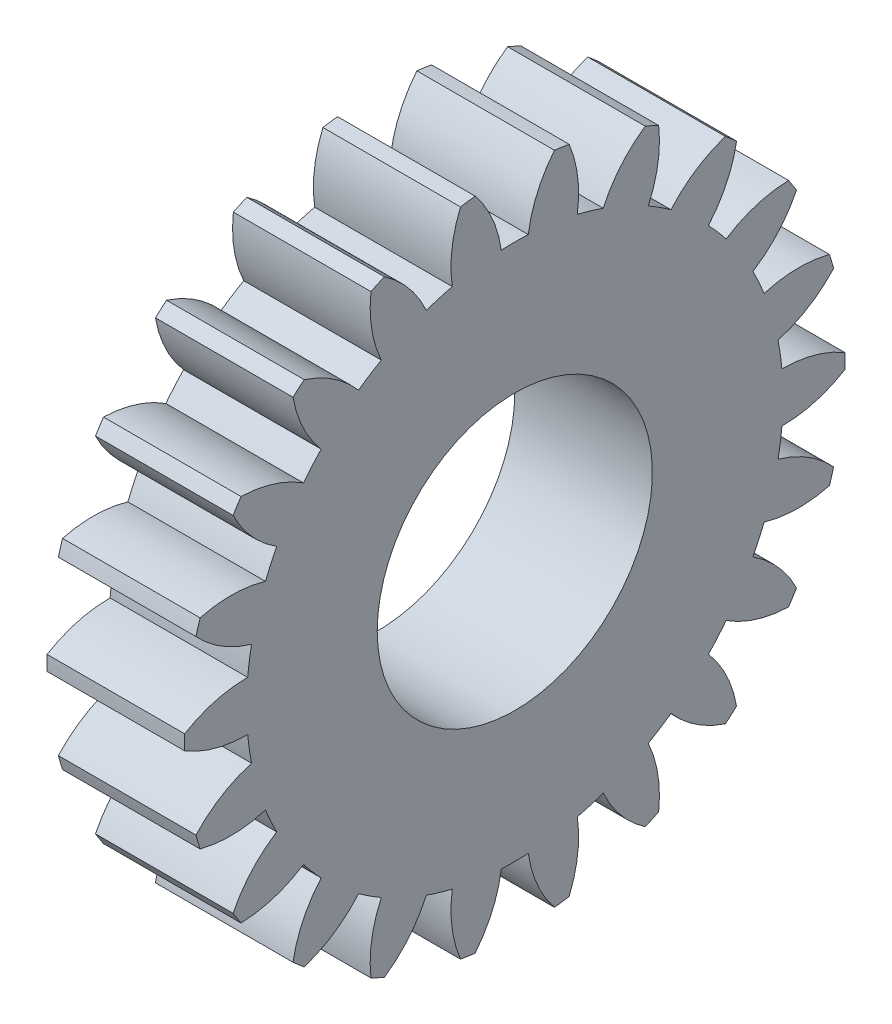
SolidWorks part; units mm, degrees
ref_plane "Plane1" through (0, 0, 0) normal (0, 0, 1) x (1, 0, 0)
ref_plane "Plane2" through (0, 0, 0) normal (0, 1, 0) x (1, 0, 0)
ref_plane "Plane3" through (0, 0, 0) normal (1, 0, 0) x (0, 0, -1)
sketch "HoldingSke" plane through (0, 0, 0) normal (0, 1, 0) x (1, 0, 0)
  line L0 (0, 0) -> (1.8544, -0.7492)
  line L1 (-15, 0) -> (100, 0) construction
  line L2 (0, 0) -> (-2.1039, 2.3779)
  line L3 (0, 0) -> (-11.863, 4.5341)
  line L4 (0, 0) -> (8.0072, 3.2351)
  line L5 (0, 0) -> (-46.8476, -17.4728)
  line L6 (0, 0) -> (-2.0724, -1.3983)
  line L7 (-2.1039, 2.3779) -> (8.6586, 51.2059)
  line L8 (-76.2, 54.61) -> (-75.3, 54.61)
  line L9 (-71.009, 38.7566) -> (-53.1078, 45.2721)
  line L10 (-76.2, 71.12) -> (104.1128, 71.12)
  line L11 (0, 0) -> (-2.5, 0)
  line L12 (-76.2, 101.6) -> (-76.181, 101.6)
  line L13 (24.9733, 27.94) -> (52.9518, 28.4284)
  line L14 (24.9733, 27.94) -> (24.9743, 27.94)
  line L15 (24.9733, 27.94) -> (100.4006, 29.5858)
  line L16 (-63.627, -0.5) -> (-12.827, -0.5)
  circle A0 centre (0, 0) radius 2.5
  circle A1 centre (0, 0) radius 4.874
  circle A2 centre (0, 0) radius 37.5
  circle A3 centre (0, 0) radius 2.5
  dimension "MHD" = 9.748
  dimension "Hub_dia" = 75
  dimension "Bore" = 5
  dimension "MBD" = 5
  dimension "Num_teeth" = 22
  dimension "Pitch" = 2
  dimension "Overall_len" = 50
  dimension "Show_teeth" = 22
  dimension "Thickness" = 2.5
  dimension "OAL" = 50.0001
  dimension "T_dim" = 0.9
  dimension "Ap" = 20
  dimension "H" = 19.05
  dimension "Pitch_radius" = 180.3128
  dimension "Width" = 2.5
  dimension "Backlash" = 0.019
  dimension "Addendum_fac" = 1
  dimension "Dedendum_fac" = 1.25
  dimension "Clearance_fac" = 0.25
  dimension "Dedendum_add" = 0.001
  dimension "Module" = 0.5
sketch "BasProSke" plane through (0, 0, 0) normal (0, 1, 0) x (1, 0, 0)
  line L0 (-10, 0) -> (60, 0) construction
  line L1 (0, 0) -> (0, 6)
  line L2 (0, 0) -> (2.5, 0)
  line L3 (2.5, 0) -> (2.5, 6)
  line L4 (2.5, 6) -> (0, 6)
  dimension "Thickness" = 2.5
  dimension "Diameter" = 12
revolve "Base-Revolve" add sketch "BasProSke" angle 360 about L0
sketch "TooCutSke" plane through (0, 0, 0) normal (1, 0, 0) x (0, 0, -1)
  line L1 (0, 0) -> (0, 107) construction
  line L2 (0, 0) -> (-0.4256, 5.4835) construction
  line L3 (0, 0) -> (-1.5621, 10.8648) construction
  line L4 (-0.4256, 5.4835) -> (-0.7811, 5.4324) construction
  arc A0 (0.2454, 4.8678) -> (-0.2454, 4.8678) centre (0, 0) ccw
  arc A1 (0.7402, 5.9798) -> (-0.7402, 5.9798) centre (0, 0) ccw
  circle A2 centre (0, 0) radius 5.5 construction
  circle A3 centre (0, 0) radius 5.1683 construction
  arc A4 (-0.2454, 4.8678) -> (-0.7402, 5.9798) centre (-2.4244, 4.5644) ccw
  arc A5 (0.7402, 5.9798) -> (0.2454, 4.8678) centre (2.4244, 4.5644) ccw
  dimension "Root_dia" = 9.748
  dimension "Overcut_dia" = 12.0508
  dimension "Pitch_dia" = 11
  dimension "Base_dia" = 10.3366
  dimension "Flank_rad" = 2.2
  dimension "Half_ang" = 8.182
  dimension "Half_CT" = 0.3591
extrude "ToothCut" cut sketch "TooCutSke" along normal through all
fillet "Breaks" [suppressed] radius 0.01
fillet "RootFillets" [suppressed] radius 0.126
pattern_circular "TeethCuts" count 22 every 16.364 about axis through (-10, 0, 0) along (1, 0, 0) of "ToothCut", "RootFillets", "Breaks"
sketch "HubNeaOneSke" plane through (0, 0, 0) normal (-1, 0, 0) x (0, 0, 1)
  circle A0 centre (0, 0) radius 4.874
  dimension "Diameter" = 9.748
extrude "HubNearOne" [suppressed] add sketch "HubNeaOneSke" along normal blind 47.5001
sketch "HubNeaBotSke" plane through (0, 0, 0) normal (-1, 0, 0) x (0, 0, 1)
  circle A0 centre (0, 0) radius 4.874
  dimension "Diameter" = 9.748
extrude "HubNearBoth" [suppressed] add sketch "HubNeaBotSke" along normal blind 23.75
ref_plane "FarPln" through (2.5, 0, 0) normal (1, 0, 0) x (0, 0, -1)
sketch "HubFarSke" plane through (2.5, 0, 0) normal (1, 0, 0) x (0, 0, -1)
  circle A0 centre (0, 0) radius 4.874
  dimension "Diameter" = 9.748
extrude "HubFar" [suppressed] add sketch "HubFarSke" along normal blind 23.75
sketch "BorSke" plane through (0, 0, 0) normal (1, 0, 0) x (0, 0, -1)
  circle A0 centre (0, 0) radius 2.5
  dimension "Diameter" = 5
extrude "Bore" cut sketch "BorSke" along normal mid plane 100.0001
sketch "KeySke" plane through (0, 0, 0) normal (1, 0, 0) x (0, 0, -1)
  line L0 (-1, 0) -> (-1, 3.4)
  line L1 (-1, 3.4) -> (1, 3.4)
  line L2 (1, 3.4) -> (1, 0)
  line L3 (0, 0) -> (0, 34) construction
  line L4 (-1, 0) -> (1, 0)
  dimension "Offset" = 3.4
  dimension "Width" = 2
extrude "Keyway" [suppressed] cut sketch "KeySke" along normal mid plane 100.0001
pattern_circular "Keyway2" [suppressed] count 2 every 90 about axis through (-10, 0, 0) along (1, 0, 0)
equation "' \"Module@HoldingSke\" = 6.35"
equation "' \"Num_teeth@HoldingSke\" = 12"
equation "' \"Ap@HoldingSke\" =  20"
equation "' \"Ap@HoldingSke\" = 20"
equation "' \"Width@HoldingSke\" = 0.5 * 25.4"
equation "' \"Hub_dia@HoldingSke\"= 1 * 25.4"
equation "' \"Hub_dia@HoldingSke\" = 1 * 25.4"
equation "' \"Overall_len@HoldingSke\" = 1.0 * 25.4"
equation "' \"Bore@HoldingSke\" = 0.75 * 25.4"
equation "' \"T_dim@HoldingSke\" = 0.1 * 25.4"
equation "' \"Width@KeySke\" = 0.25 * 25.4"
equation "' \"Show_teeth@HoldingSke\" = 13"
equation "' \"Backlash@HoldingSke\" = 0.009 * 25.4"
equation "' \"Addendum_fac@HoldingSke\" = 1.0"
equation "' \"Dedendum_fac@HoldingSke\" = 1.25"
equation "' \"Dedendum_add@HoldingSke\" = 0.00005 * 25.4"
equation "' \"Clearance_fac@HoldingSke\" = 0.25"
equation "\"Pitch@HoldingSke\" = 1 / \"Module@HoldingSke\""
equation "\"Overcut_dia@TooCutSke\" = (\"Num_teeth@HoldingSke\" + 2 * \"Addendum_fac@HoldingSke\") / \"Pitch@HoldingSke\" + 0.002 * 25.4"
equation "\"Pitch_dia@TooCutSke\" = \"Num_teeth@HoldingSke\" / \"Pitch@HoldingSke\""
equation "\"Base_dia@TooCutSke\" = \"Num_teeth@HoldingSke\" / \"Pitch@HoldingSke\" * cos((\"Ap@HoldingSke\"  * 3.14159265 / 180))"
equation "\"Root_dia@TooCutSke\" = (\"Num_teeth@HoldingSke\" + 2) / \"Pitch@HoldingSke\" - 2 * (\"Addendum_fac@HoldingSke\" + \"Dedendum_fac@HoldingSke\") / \"Pitch@HoldingSke\" - \"Dedendum_add@HoldingSke\" * 2"
equation "\"Half_ang@TooCutSke\" = 180 / \"Num_teeth@HoldingSke\""
equation "\"Half_CT@TooCutSke\" = \"Num_teeth@HoldingSke\" / \"Pitch@HoldingSke\" * sin((3.14159265 / 2 / \"Num_teeth@HoldingSke\")) / 2 - 7 * \"Backlash@HoldingSke\" / 4"
equation "\"Flank_rad@TooCutSke\" = \"Num_teeth@HoldingSke\" / \"Pitch@HoldingSke\" / 5"
equation "\"Radius@RootFillets\" = \"Clearance_fac@HoldingSke\" / \"Pitch@HoldingSke\" + \"Dedendum_add@HoldingSke\""
equation "\"Break_rad@Breaks\" = 0.02 / \"Pitch@HoldingSke\""
equation "\"Thickness@HoldingSke\" = \"Width@HoldingSke\""
equation "\"OAL@HoldingSke\" = \"Thickness@HoldingSke\""
equation "\"MHD@HoldingSke\" = (\"Num_teeth@HoldingSke\" + 2) / \"Pitch@HoldingSke\" - 2 * (\"Addendum_fac@HoldingSke\" + \"Dedendum_fac@HoldingSke\")  / \"Pitch@HoldingSke\" - \"Dedendum_add@HoldingSke\" * 2"
equation "\"MBD@HoldingSke\" = (\"Num_teeth@HoldingSke\" + 2) / \"Pitch@HoldingSke\" - 2 * (\"Addendum_fac@HoldingSke\" + \"Dedendum_fac@HoldingSke\")  / \"Pitch@HoldingSke\" - \"Dedendum_add@HoldingSke\" * 2 - 0.002 * 25.4"
equation "\"MHD@HoldingSke\" = ((sgn( \"MHD@HoldingSke\" - \"Hub_dia@HoldingSke\" )-1)*( \"MHD@HoldingSke\" - \"Hub_dia@HoldingSke\" ))/-2+ \"Hub_dia@HoldingSke\""
equation "\"MBD@HoldingSke\" = ((sgn( \"MBD@HoldingSke\" - \"Bore@HoldingSke\" )-1)*( \"MBD@HoldingSke\" - \"Bore@HoldingSke\" ))/-2+ \"Bore@HoldingSke\""
equation "\"OAL@HoldingSke\" = ((sgn( \"OAL@HoldingSke\" - \"Overall_len@HoldingSke\" )+1)*( \"OAL@HoldingSke\" - \"Overall_len@HoldingSke\" ))/2 + \"Overall_len@HoldingSke\" + 0.000002 * 25.4"
equation "\"Num_teeth@TeethCuts\" = int( \"Show_teeth@HoldingSke\" ) + 1"
equation "\"Num_teeth@TeethCuts\" = ((sgn( \"Num_teeth@TeethCuts\" - \"Num_teeth@HoldingSke\" )-1)*( \"Num_teeth@TeethCuts\" - \"Num_teeth@HoldingSke\" ))/-2+ \"Num_teeth@HoldingSke\""
equation "\"Num_teeth@TeethCuts\" = ((sgn( \"Num_teeth@TeethCuts\" - 2.0)+1)*( \"Num_teeth@TeethCuts\" - 2.0))/2 +2.0"
equation "\"Angle@TeethCuts\" = 360.0 / \"Num_teeth@HoldingSke\""
equation "\"Diameter@BasProSke\" = (\"Num_teeth@HoldingSke\" + 2 * \"Addendum_fac@HoldingSke\") / \"Pitch@HoldingSke\""
equation "\"Thickness@BasProSke\"  = \"Thickness@HoldingSke\""
equation "' \"Fillet_rad@BasProSke\" =  \"Thickness@HoldingSke\" * 0.05"
equation "' \"Fillet_rad@BasProSke\" = \"Thickness@HoldingSke\" * 0.05"
equation "\"MHD@HoldingSke\" = ((sgn( \"MHD@HoldingSke\" - \"Root_dia@TooCutSke\" )-1)*( \"MHD@HoldingSke\" - \"Root_dia@TooCutSke\" ))/-2+ \"Root_dia@TooCutSke\""
equation "\"Diameter@HubNeaOneSke\" = \"MHD@HoldingSke\""
equation "\"Length@HubNearOne\" = \"OAL@HoldingSke\" - \"Thickness@BasProSke\""
equation "\"Diameter@HubNeaBotSke\" = \"MHD@HoldingSke\""
equation "\"Length@HubNearBoth\" = ( \"OAL@HoldingSke\" - \"Thickness@BasProSke\" ) / 2.0"
equation "\"Thickness@FarPln\" = \"Thickness@BasProSke\""
equation "\"Diameter@HubFarSke\" = \"MHD@HoldingSke\""
equation "\"Length@HubFar\" = ( \"OAL@HoldingSke\" - \"Thickness@BasProSke\" ) / 2.0"
equation "\"Diameter@BorSke\" = \"MBD@HoldingSke\""
equation "\"D1@Bore\" = \"OAL@HoldingSke\" * 2.0"
equation "\"D1@Keyway\" = \"OAL@HoldingSke\" * 2.0"
equation "\"Offset@KeySke\" = \"T_dim@HoldingSke\" + \"MBD@HoldingSke\" / 2.0"
